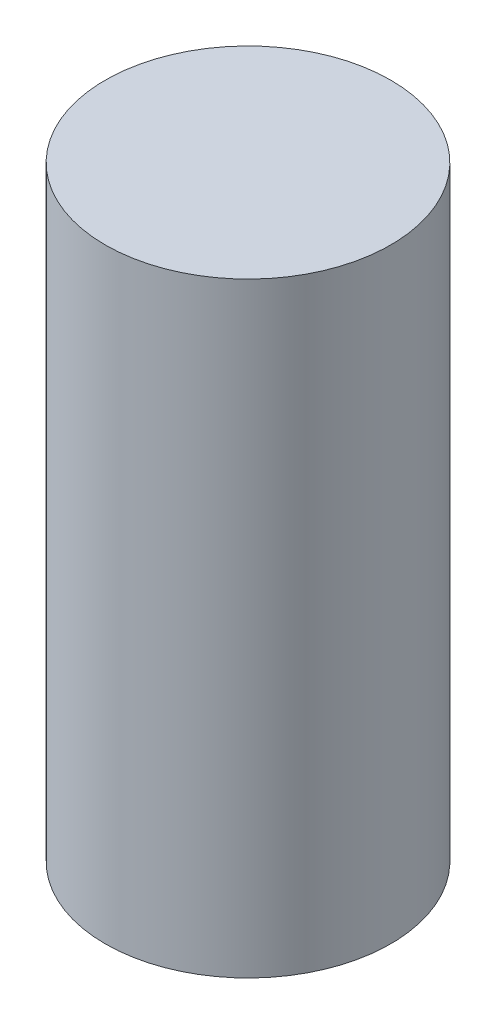
SolidWorks part; units mm, degrees
material "Silicon"
ref_plane "Front Plane" through (0, 0, 0) normal (0, 0, 1) x (1, 0, 0)
ref_plane "Top Plane" through (0, 0, 0) normal (0, 1, 0) x (1, 0, 0)
ref_plane "Right Plane" through (0, 0, 0) normal (1, 0, 0) x (0, 0, -1)
sketch "Main Parachute Bag Profile" plane through (0, 0, 0) normal (0, 1, 0) x (1, 0, 0)
  circle A0 centre (0, 0) radius 63.5
  dimension "D1" = 127
extrude "Main Parachute Bag Body" add sketch "Main Parachute Bag Profile" along normal blind 269.24 contours A0
equation "\"Packed Length\"= 10.6"
equation "\"Packed Diameter\"= 5"
equation "\"D1@Main Parachute Bag Body\"=\"Packed Length\""
